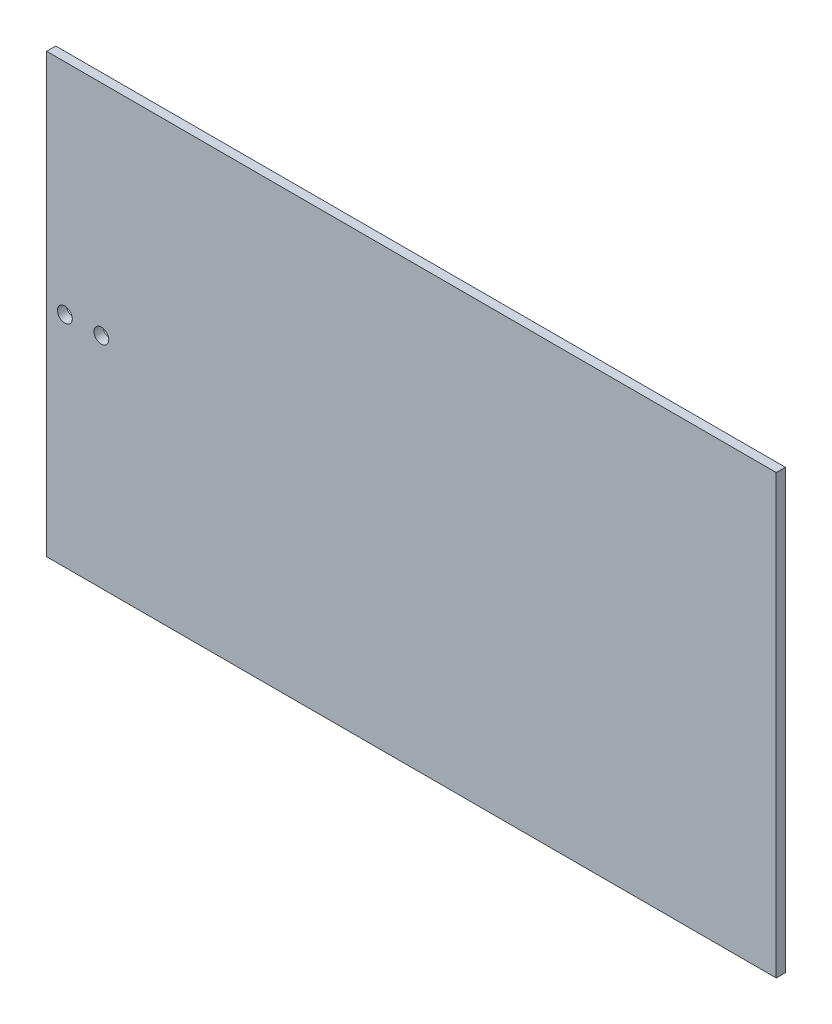
SolidWorks part; units mm, degrees
ref_plane "Front Plane" through (0, 0, 0) normal (0, 0, 1) x (1, 0, 0)
ref_plane "Top Plane" through (0, 0, 0) normal (0, 1, 0) x (1, 0, 0)
ref_plane "Right Plane" through (0, 0, 0) normal (1, 0, 0) x (0, 0, -1)
sketch "Sketch1" plane through (0, 0, 0) normal (0, 0, 1) x (1, 0, 0)
  line L1 (-158.8654, 64.9705) -> (95.1346, 64.9705)
  line L2 (-158.8654, 64.9705) -> (-158.8654, -87.4295)
  line L3 (-158.8654, -87.4295) -> (95.1346, -87.4295)
  line L4 (95.1346, 64.9705) -> (95.1346, -87.4295)
  dimension "D1" = 152.4
  dimension "D2" = 254
extrude "Boss-Extrude1" add sketch "Sketch1" along normal blind 3.175
sketch "Sketch2" plane through (0, 0, 3.175) normal (0, 0, 1) x (1, 0, 0)
  line L0 (-158.8654, 64.9705) -> (-158.8654, -87.4295) construction
  circle A0 centre (-152.5154, -11.2295) radius 2.5797
  circle A1 centre (-139.8154, -11.2295) radius 2.5797
  point P6 (-158.8654, -11.2295)
  point P7 (0, 0)
  dimension "D1" = 5.1594
  dimension "D2" = 5.1594
  dimension "D3" = 6.35
  dimension "D4" = 19.05
extrude "Cut-Extrude1" cut sketch "Sketch2" against normal blind 3.175
